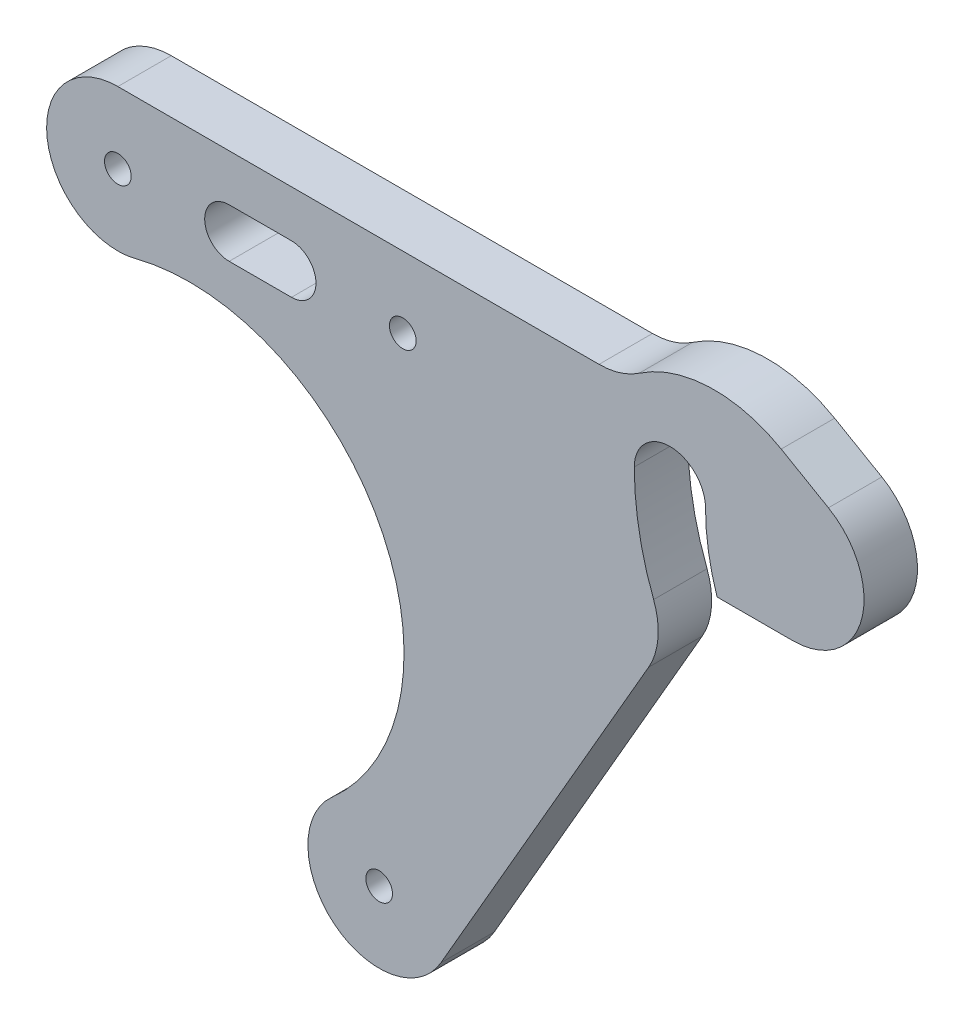
SolidWorks part; units mm, degrees
material "Balsa"
ref_plane "Front Plane" through (0, 0, 0) normal (0, 0, 1) x (1, 0, 0)
ref_plane "Top Plane" through (0, 0, 0) normal (0, 1, 0) x (1, 0, 0)
ref_plane "Right Plane" through (0, 0, 0) normal (1, 0, 0) x (0, 0, -1)
sketch "Sketch1" plane through (0, 0, 0) normal (0, 0, 1) x (1, 0, 0)
  line L0 (-49.5, 2.75) -> (-42.5, 2.75)
  line L1 (-62, 0) -> (-30, 0) construction
  line L2 (0, 0) -> (4, 0)
  line L3 (-42.5, -2.75) -> (-49.5, -2.75)
  line L4 (5.3008, -8) -> (13.8053, -8)
  line L5 (-7.9602, 8) -> (-62, 8)
  line L6 (-25.7245, -59.0949) -> (-2.3791, -18.6594)
  line L11 (46.5706, -24.3203) -> (60.9988, -15.9901)
  line L12 (45.9987, 9.9906) -> (33.5801, 2.8207)
  line L13 (24.9199, 2.8206) -> (12.5012, 9.9904)
  line L14 (-2.4986, -15.9904) -> (11.9296, -24.3204)
  line L17 (17.8052, 6.9282) -> (12.5012, 9.9904)
  arc A0 (4, 0) -> (-4, 0) centre (0, 0) ccw
  arc A1 (-49.5, 2.75) -> (-49.5, -2.75) centre (-49.5, 0) ccw
  arc A2 (-3.4519, 9.3913) -> (-7.9602, 8) centre (-7.9602, 16) cw
  circle A3 centre (-30, 0) radius 1.5
  circle A4 centre (-32.6527, -55.0949) radius 1.5
  circle A5 centre (-62, 0) radius 1.5
  arc A6 (-62, 8) -> (-68.8243, 4.1748) centre (-62, 0) ccw
  arc A7 (-4, 0) -> (-1.8295, -11.8164) centre (29.25, 0) ccw
  arc A8 (4, 0) -> (5.3008, -8) centre (29.25, 0) ccw
  arc A11 (-39.7407, -58.8044) -> (-25.7245, -59.0949) centre (-32.6527, -55.0949) ccw
  arc A12 (-2.3791, -18.6594) -> (-1.8295, -11.8164) centre (-9.3073, -14.6594) ccw
  arc A13 (-68.8243, 4.1748) -> (-59.997, -7.7452) centre (-62, 0) ccw
  arc A14 (-39.7407, -58.8044) -> (-38.0114, -49.1549) centre (-32.6527, -55.0949) cw
  arc A15 (-38.0114, -49.1549) -> (-59.997, -7.7452) centre (-53.9619, -31.0822) ccw
  arc A16 (-42.5, -2.75) -> (-42.5, 2.75) centre (-42.5, 0) ccw
  arc A17 (13.8053, -8) -> (17.8052, 6.9282) centre (13.8053, 0) ccw
  arc A19 (11.9296, -24.3204) -> (46.5706, -24.3203) centre (29.25, 5.6796) ccw
  arc A20 (60.9988, -15.9901) -> (45.9987, 9.9906) centre (53.4987, -2.9997) ccw
  arc A21 (24.9199, 2.8206) -> (33.5801, 2.8207) centre (29.2499, 10.3207) ccw
  arc A22 (12.5012, 9.9904) -> (-2.4986, -15.9904) centre (5.0013, -3) ccw
  arc A26 (12.5012, 9.9904) -> (-3.4519, 9.3913) centre (5.0013, -3) ccw
  point P27 (-33.5098, -71.6906)
  dimension "D1" = 8
  dimension "D3" = 8
  dimension "D4" = 16
  dimension "D5" = 3
  dimension "D6" = 3
  dimension "D7" = 30
  dimension "D8" = 12.5
  dimension "D9" = 63.0949
  dimension "D10" = 5.5
  dimension "D11" = 0
  dimension "D14" = 8
  dimension "D15" = 19.5
  dimension "D16" = 12.5
  dimension "D13" = 3
  dimension "D2" = 8
  dimension "D12" = 60
  dimension "D17" = 0
extrude "Boss-Extrude1" add sketch "Sketch1" along normal blind 6
